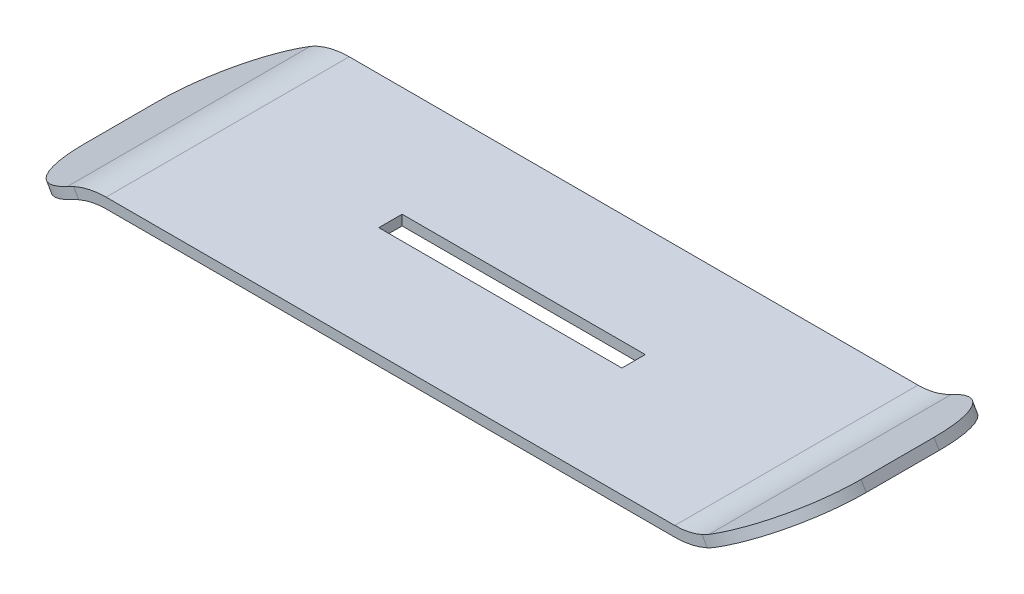
SolidWorks part; units mm, degrees
ref_plane "Front Plane" through (0, 0, 0) normal (0, 0, 1) x (1, 0, 0)
ref_plane "Top Plane" through (0, 0, 0) normal (0, 1, 0) x (1, 0, 0)
ref_plane "Right Plane" through (0, 0, 0) normal (1, 0, 0) x (0, 0, -1)
sketch "Sketch1" plane through (0, 0, 0) normal (0, 0, 1) x (1, 0, 0)
  line L0 (-26.5723, 0) -> (26.6434, 0) construction
  line L1 (0, 17.1583) -> (0, -16.4478) construction
  line L2 (-29.7082, 0) -> (29.7082, 0)
  line L3 (33.5182, 1.0209) -> (40.5488, 5.08)
  line L4 (-33.5182, -1.0209) -> (-40.5488, -5.08)
  arc A0 (29.7082, 0) -> (33.5182, 1.0209) centre (29.7082, 7.62) ccw
  arc A1 (-29.7082, 0) -> (-33.5182, -1.0209) centre (-29.7082, -7.62) ccw
  point P11 (31.75, 0)
  point P14 (-31.75, 0)
  dimension "D6" = 7.62
  dimension "D1" = 5.08
  dimension "D2" = 63.5
  dimension "D3" = 5.08
  dimension "D4" = 30
  dimension "D5" = 30
extrude "Extrude-Thin1" add sketch "Sketch1" along normal mid plane 25.4 thin thin type mid plane wall 1.0668
fillet "Fillet1" radius 8.89 4 edges at (40.5488, 5.08, -12.7) (40.5488, 5.08, 12.7) (-40.5488, -5.08, -12.7) (-40.5488, -5.08, 12.7)
sketch "Sketch2" plane through (0, 0.5334, 0) normal (0, 1, 0) x (1, 0, 0)
  line L1 (-12.7, 1.2192) -> (12.7, 1.2192)
  line L2 (-12.7, 1.2192) -> (-12.7, -1.2192)
  line L3 (-12.7, -1.2192) -> (12.7, -1.2192)
  line L4 (12.7, 1.2192) -> (12.7, -1.2192)
  line L5 (-12.7, 1.2192) -> (12.7, -1.2192) construction
  line L6 (-12.7, -1.2192) -> (12.7, 1.2192) construction
  point P0 (0, 0)
  dimension "D1" = 25.4
  dimension "D2" = 2.4384
extrude "Cut-Extrude1" cut sketch "Sketch2" against normal through all
